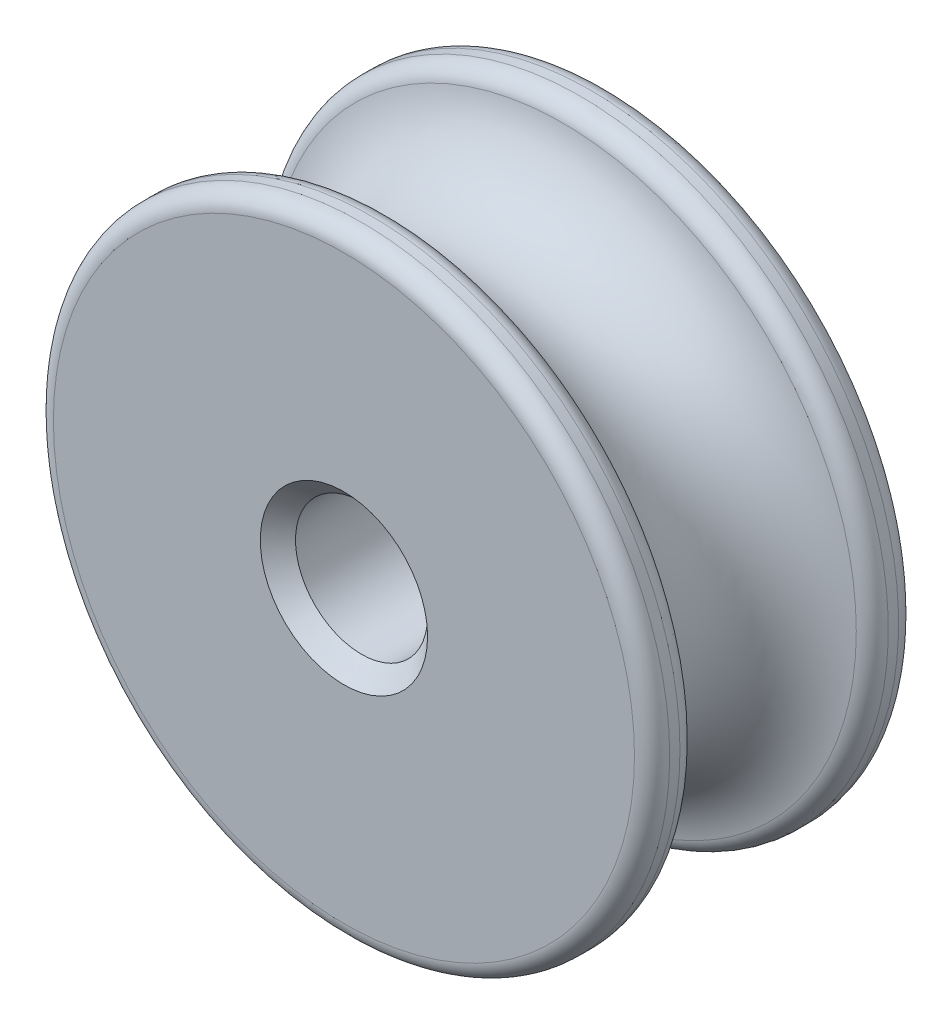
SolidWorks part; units mm, degrees
ref_plane "Front" through (0, 0, 0) normal (0, 0, 1) x (1, 0, 0)
ref_plane "Top" through (0, 0, 0) normal (0, 1, 0) x (1, 0, 0)
ref_plane "Right" through (0, 0, 0) normal (1, 0, 0) x (0, 0, -1)
sketch "Sketch1" plane through (0, 0, 0) normal (0, 1, 0) x (1, 0, 0)
  line L0 (8.89, 6.35) -> (8.89, 7.62)
  line L1 (0, 0) -> (8.89, 0)
  line L2 (0, 0) -> (0, 7.62)
  line L3 (0, 7.62) -> (8.89, 7.62)
  line L4 (8.89, 0) -> (8.89, 1.27)
  arc A0 (8.89, 1.27) -> (8.89, 6.35) centre (8.89, 3.81) cw
  dimension "D1" = 8.89
  dimension "D2" = 7.62
  dimension "D3" = 1.27
revolve "Revolve1" add sketch "Sketch1" angle 360 about L2
fillet "Fillet1" radius 0.508 4 edges at (8.89, 0, -7.62) (8.89, 0, -6.35) (8.89, 0, 0) (8.89, 0, -1.27)
sketch "Sketch2" plane through (0, 0, 0) normal (0, 0, 1) x (1, 0, 0)
  circle A0 centre (0, 0) radius 1.905
  dimension "D1" = 3.81
extrude "Cut-Extrude1" cut sketch "Sketch2" against normal through all
chamfer "Chamfer1" distance 0.508 angle 45 2 edges at (1.905, 0, 0) (1.905, 0, -7.62)
